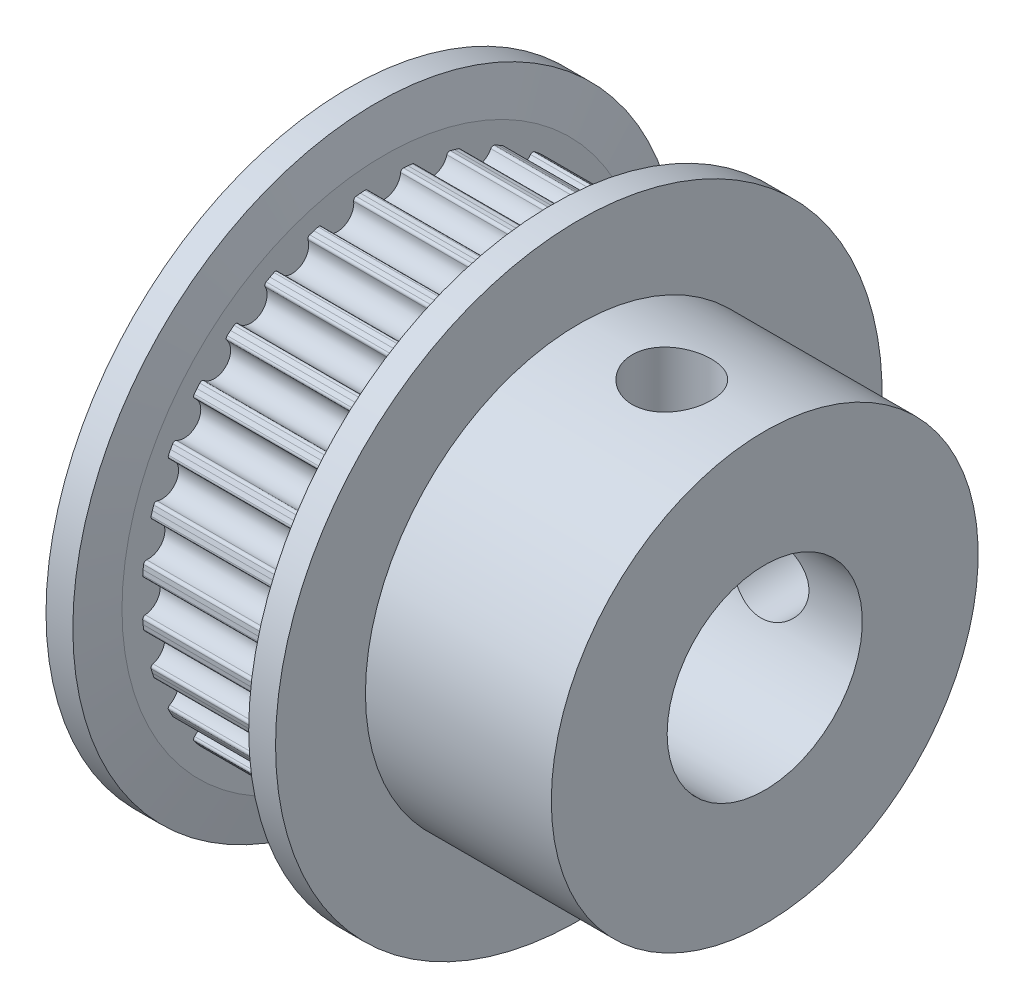
SolidWorks part; units mm, degrees
ref_plane "Front Plane" through (0, 0, 0) normal (0, 0, 1) x (1, 0, 0)
ref_plane "Top Plane" through (0, 0, 0) normal (0, 1, 0) x (1, 0, 0)
ref_plane "Right Plane" through (0, 0, 0) normal (1, 0, 0) x (0, 0, -1)
ref_plane "Plane1" through (0, 0, 0) normal (0, 0, 1) x (1, 0, 0)
sketch "Sketch1" plane through (0, 0, 0) normal (0, 0, 1) x (1, 0, 0)
  line L0 (0, 0) -> (0, 8.75)
  line L1 (0, 8.75) -> (1.43, 8.75)
  line L2 (1.43, 8.75) -> (1.43, 10.0881)
  line L3 (1.43, 10.0881) -> (7.98, 10.0881)
  line L4 (7.98, 10.0881) -> (7.98, 8.75)
  line L5 (7.98, 8.75) -> (17.03, 8.75)
  line L6 (17.03, 8.75) -> (17.03, 0)
  line L7 (17.03, 0) -> (0, 0)
  line L8 (17.03, 0) -> (0, 0) construction
  dimension "D1" = 6.55
  dimension "D2" = 8.75
  dimension "D3" = 1.43
  dimension "D4" = 9.05
  dimension "D5" = 10.0881
revolve "Revolve1" add sketch "Sketch1" angle 360 about L8
sketch "Sketch2" plane through (1.43, 0, 0) normal (1, 0, 0) x (0, 0, -1)
  line L0 (-1.0344, 9.88) -> (-1.0578, 10.1299)
  line L1 (-0.793, 9.8993) -> (-1.0344, 9.88)
  line L2 (0.793, 9.8993) -> (1.0344, 9.88)
  line L3 (1.0344, 9.88) -> (1.0578, 10.1299)
  line L4 (0, 10.185) -> (0, 0) construction
  arc A0 (-0.6724, 9.7974) -> (-0.793, 9.8993) centre (-0.784, 9.7876) ccw
  arc A1 (-0.6724, 9.7974) -> (0.6724, 9.7974) centre (0, 9.856) ccw
  arc A2 (0.6724, 9.7974) -> (0.793, 9.8993) centre (0.784, 9.7876) cw
  arc A3 (1.0578, 10.1299) -> (-1.0578, 10.1299) centre (0, 0) ccw
  dimension "D2" = 0.675
  dimension "D1" = 9.856
  dimension "D3" = 9.931
extrude "Cut-Extrude1" cut sketch "Sketch2" against normal up to surface
ref_axis "Axis1" through (17.03, 0, 0) along (-1, 0, 0)
pattern_circular "CirPattern1" count 32 over 360 about axis through (0, 0, 0) along (1, 0, 0) of "Cut-Extrude1"
sketch "Sketch34" plane through (0, 0, 0) normal (0, 0, 1) x (1, 0, 0)
  line L0 (7.98, 8.75) -> (7.98, 10.75)
  line L1 (7.98, 10.75) -> (8.31, 12.435)
  line L2 (8.31, 12.435) -> (9.41, 12.435)
  line L3 (9.41, 12.435) -> (9.41, 8.75)
  line L4 (17.03, 8.75) -> (7.98, 8.75) construction
  line L5 (9.41, 8.75) -> (7.98, 8.75)
  line L6 (17.03, 0) -> (7.98, 0) construction
  line L7 (1.43, 8.75) -> (1.43, 10.75)
  line L8 (1.43, 10.75) -> (1.1, 12.435)
  line L9 (1.1, 12.435) -> (0, 12.435)
  line L10 (0, 12.435) -> (0, 8.76)
  line L11 (0.01, 8.75) -> (1.43, 8.75)
  line L12 (0, 8.76) -> (0.01, 8.75)
  point P16 (0, 8.75)
  dimension "D1" = 1.43
  dimension "D2" = 12.435
  dimension "D3" = 1.1
  dimension "D4" = 10.75
revolve "Revolve2" add sketch "Sketch34" angle 360 about L6
sketch "Sketch39" plane through (0, 0, 0) normal (-1, 0, 0) x (0, 0, 1)
  circle A0 centre (0, 0) radius 4.001
  dimension "D1" = 8.002
extrude "Cut-Extrude2" cut sketch "Sketch39" against normal up to surface (17.03 mm away) up to face at (17.03, 0, 8.75)
ref_plane "Plane39" through (13.22, 0, 0) normal (1, 0, 0) x (0, 0, -1)
sketch "Sketch37" plane through (13.22, 0, 0) normal (1, 0, 0) x (0, 0, -1)
  line L0 (0, 9.93) -> (1.621, 9.93)
  line L1 (1.621, 9.93) -> (1.621, 0)
  line L2 (1.621, 0) -> (0, 0)
  line L3 (0, 0) -> (0, 9.93)
  line L4 (0, 0) -> (0, 9.93) construction
revolve "Cut-Revolve2" cut sketch "Sketch37" angle 360 about L4
pattern_circular "CirPattern2" count 2 over 90 about axis through (17.03, 0, 0) along (-1, 0, 0) of "Cut-Revolve2"
ref_plane "Plane40" through (4.705, 0, 0) normal (-1, 0, 0) x (0, 0, 1)
